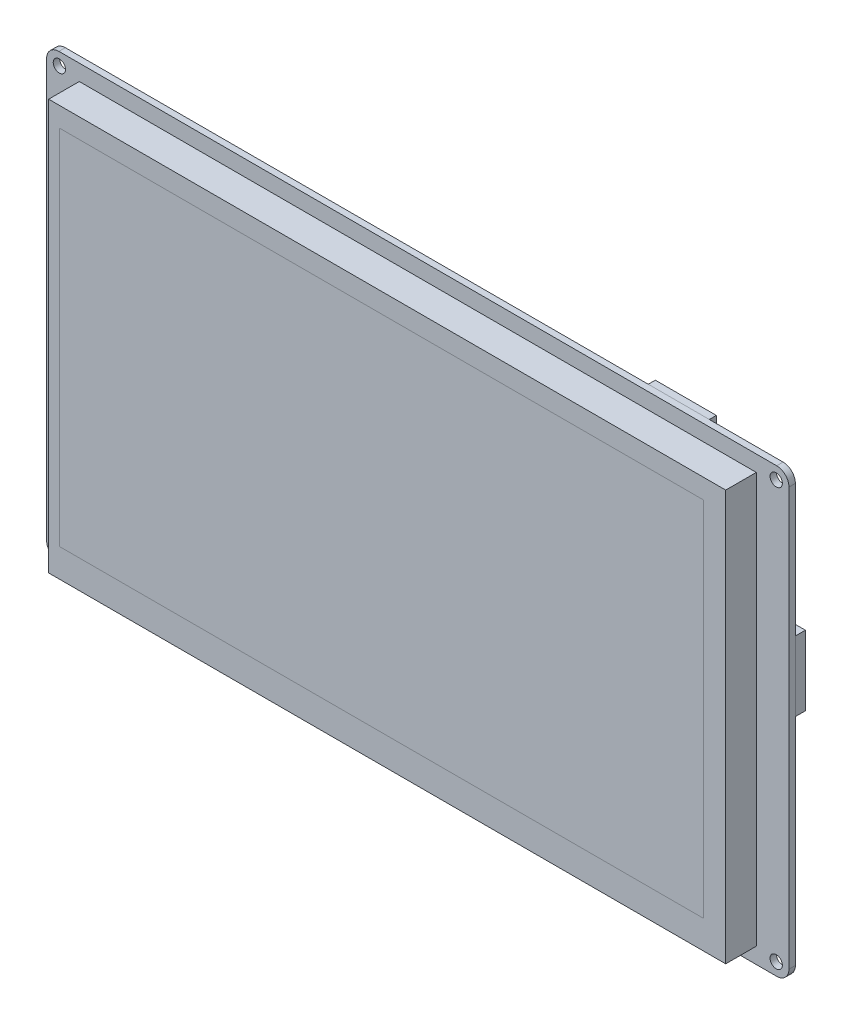
SolidWorks part; units mm, degrees
other "PCB"
other "Display"
other "Connector"
other "SD Card Socket"
other "GPIO Connector"
other "Screen"
ref_plane "Front Plane" through (0, 0, 0) normal (0, 0, 1) x (1, 0, 0)
ref_plane "Top Plane" through (0, 0, 0) normal (0, 1, 0) x (1, 0, 0)
ref_plane "Right Plane" through (0, 0, 0) normal (1, 0, 0) x (0, 0, -1)
sketch "Sketch1" plane through (0, 0, 0) normal (0, 0, 1) x (1, 0, 0)
  line L0 (0, 0) -> (90.46, 0) construction
  line L1 (-90.46, 53.88) -> (90.46, 53.88)
  line L2 (-90.46, 53.88) -> (-90.46, -53.88)
  line L3 (-90.46, -53.88) -> (90.46, -53.88)
  line L4 (90.46, 53.88) -> (90.46, -53.88)
  line L5 (-90.46, 53.88) -> (90.46, -53.88) construction
  line L6 (-90.46, -53.88) -> (90.46, 53.88) construction
  line L7 (0, 0) -> (0, 53.88) construction
  circle A0 centre (87.35, 50.85) radius 1.5
  circle A1 centre (87.35, -50.85) radius 1.5
  circle A2 centre (-87.35, 50.85) radius 1.5
  circle A3 centre (-87.35, -50.85) radius 1.5
  point P0 (0, 0)
  dimension "D3" = 3
  dimension "D1" = 180.92
  dimension "D2" = 107.76
  dimension "D4" = 101.7
  dimension "D5" = 174.7
extrude "Boss-Extrude1" add sketch "Sketch1" along normal blind 1.56
sketch "Sketch2" plane through (0, 0, 1.56) normal (0, 0, 1) x (1, 0, 0)
  line L1 (-82.5, 50) -> (82.5, 50)
  line L2 (-82.5, 50) -> (-82.5, -50)
  line L3 (-82.5, -50) -> (82.5, -50)
  line L4 (82.5, 50) -> (82.5, -50)
  line L5 (-82.5, 50) -> (82.5, -50) construction
  line L6 (-82.5, -50) -> (82.5, 50) construction
  point P0 (0, 0)
  dimension "D1" = 165
  dimension "D2" = 100
extrude "Boss-Extrude2" add sketch "Sketch2" along normal blind 7.46 separate body
sketch "Sketch3" plane through (0, 0, 0) normal (0, 0, -1) x (-1, 0, 0)
  line L0 (0, 0) -> (90.46, 0) construction
  line L1 (82.66, 7.44) -> (90.46, 7.44)
  line L2 (82.66, 7.44) -> (82.66, -7.44)
  line L3 (82.66, -7.44) -> (90.46, -7.44)
  line L4 (90.46, 7.44) -> (90.46, -7.44)
  line L5 (82.66, 7.44) -> (90.46, -7.44) construction
  line L6 (82.66, -7.44) -> (90.46, 7.44) construction
  line L7 (90.46, 53.88) -> (90.46, -53.88) construction
  point P0 (86.56, 0)
  dimension "D1" = 14.88
  dimension "D2" = 7.8
extrude "Boss-Extrude3" add sketch "Sketch3" along normal blind 5.96 separate body
sketch "Sketch4" plane through (0, 0, 0) normal (0, 0, -1) x (-1, 0, 0)
  line L0 (-90.46, 53.88) -> (90.46, 53.88) construction
  line L1 (-69.48, 53.88) -> (-54.61, 53.88)
  line L2 (-69.48, 53.88) -> (-69.48, 38.98)
  line L3 (-69.48, 38.98) -> (-54.61, 38.98)
  line L4 (-54.61, 53.88) -> (-54.61, 38.98)
  line L5 (-90.46, -53.88) -> (-90.46, 53.88) construction
  dimension "D1" = 20.98
  dimension "D2" = 14.87
  dimension "D3" = 14.9
extrude "Boss-Extrude4" add sketch "Sketch4" along normal blind 1.72 separate body
sketch "Sketch5" plane through (0, 0, 0) normal (0, 0, -1) x (-1, 0, 0)
  line L0 (-90.46, -53.88) -> (-90.46, 53.88) construction
  line L1 (-90.46, 18.68) -> (-85, 18.68)
  line L2 (-90.46, 18.68) -> (-90.46, 1.66)
  line L3 (-90.46, 1.66) -> (-85, 1.66)
  line L4 (-85, 18.68) -> (-85, 1.66)
  line L5 (-90.46, 53.88) -> (90.46, 53.88) construction
  dimension "D1" = 35.2
  dimension "D2" = 17.02
  dimension "D3" = 5.46
extrude "Boss-Extrude5" add sketch "Sketch5" along normal blind 2.44 separate body
sketch "Sketch6" plane through (0, 0, 0) normal (0, 0, -1) x (-1, 0, 0)
  line L0 (-90.46, -53.88) -> (-90.46, 53.88) construction
  line L1 (-61.98, -46.54) -> (51.04, -46.54)
  line L2 (-61.98, -46.54) -> (-61.98, -49.54)
  line L3 (-61.98, -49.54) -> (51.04, -49.54)
  line L4 (51.04, -46.54) -> (51.04, -49.54)
  line L5 (90.46, -53.88) -> (-90.46, -53.88) construction
  dimension "D1" = 113.02
  dimension "D2" = 3
  dimension "D3" = 28.48
  dimension "D4" = 4.34
extrude "Cut-Extrude1" cut sketch "Sketch6" against normal up to next (1.56 mm away)
sketch "Sketch7" plane through (0, 0, 9.02) normal (0, 0, 1) x (1, 0, 0)
  line L1 (-79.8, 45.31) -> (77.2, 45.31)
  line L2 (-79.8, 45.31) -> (-79.8, -43)
  line L3 (-79.8, -43) -> (77.2, -43)
  line L4 (77.2, 45.31) -> (77.2, -43)
  line L5 (82.5, -50) -> (82.5, 50) construction
  line L6 (-82.5, -50) -> (82.5, -50) construction
  dimension "D1" = 157
  dimension "D2" = 88.31
  dimension "D3" = 5.3
  dimension "D4" = 7
ref_plane "Plane1" through (0, 0, 9.12) normal (0, 0, 1) x (1, 0, 0)
sketch "Sketch8" plane through (0, 0, 9.12) normal (0, 0, 1) x (1, 0, 0)
  line L3 (-79.8, -43) -> (77.2, -43) construction
  line L5 (-79.8, 45.31) -> (-79.8, -43) construction
  line L6 (77.2, 45.31) -> (77.2, -43) construction
  line L7 (-79.8, 45.31) -> (77.2, 45.31) construction
  line L8 (-79.8, 45.31) -> (-79.8, -43)
  line L9 (-79.8, -43) -> (77.2, -43)
  line L10 (77.2, 45.31) -> (77.2, -43)
  line L11 (-79.8, 45.31) -> (77.2, 45.31)
surface "Surface-Plane2" sketch "Sketch8"
fillet "Fillet1" radius 3 4 edges at (90.46, 53.88, 0.78) (90.46, -53.88, 0.78) (-90.46, -53.88, 0.78) (-90.46, 53.88, 0.78)
